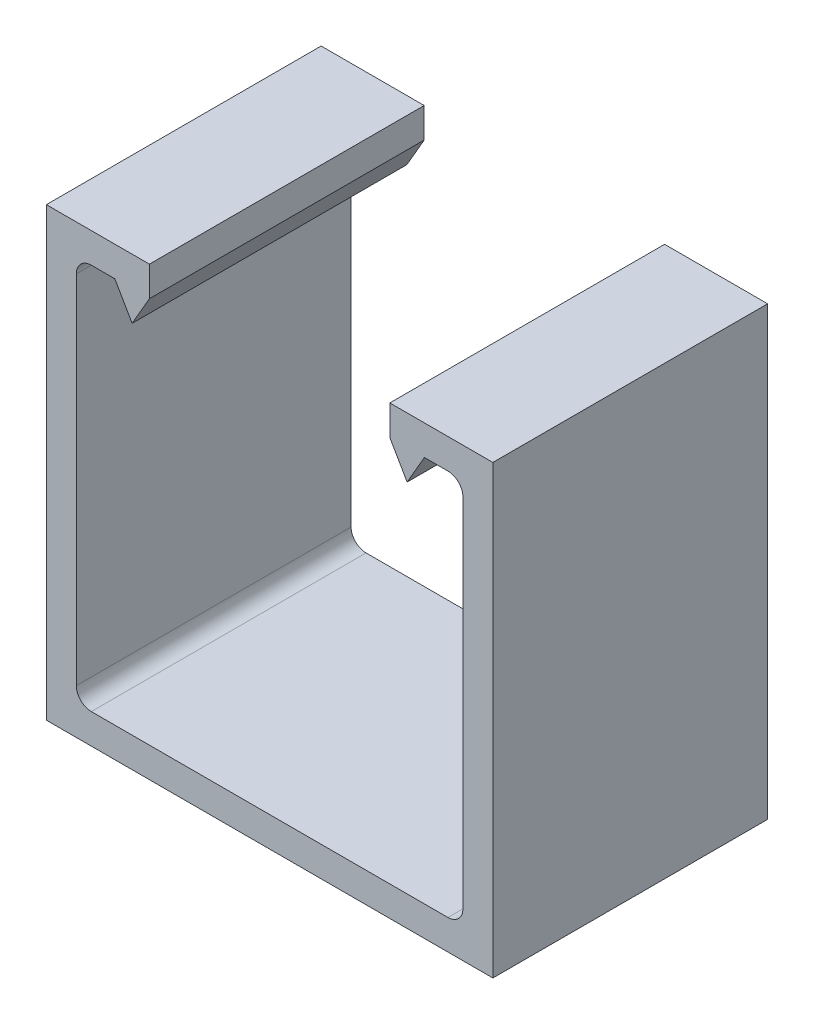
SolidWorks part; units mm, degrees
ref_plane "Plane1" through (0, 0, 0) normal (0, 0, 1) x (1, 0, 0)
ref_plane "Plane2" through (0, 0, 0) normal (0, 1, 0) x (1, 0, 0)
ref_plane "Plane3" through (0, 0, 0) normal (1, 0, 0) x (0, 0, -1)
sketch "Sketch1" plane through (0, 0, 0) normal (0, 0, 1) x (1, 0, 0)
  line L0 (-11.1125, 20.6375) -> (-20.6375, 20.6375)
  line L1 (-20.6375, 20.6375) -> (-20.6375, -20.6375)
  line L2 (-20.6375, -20.6375) -> (20.6375, -20.6375)
  line L3 (20.6375, -20.6375) -> (20.6375, 20.6375)
  line L4 (20.6375, 20.6375) -> (11.1125, 20.6375)
  line L5 (16.4846, 17.8689) -> (14.3094, 17.8689)
  line L6 (17.8689, -16.4846) -> (17.8689, 16.4846)
  line L7 (-16.4846, -17.8689) -> (16.4846, -17.8689)
  line L8 (-17.8689, 16.4846) -> (-17.8689, -16.4846)
  line L9 (-14.3094, 17.8689) -> (-16.4846, 17.8689)
  line L10 (14.3094, 17.8689) -> (12.711, 15.1003)
  line L11 (12.711, 15.1003) -> (11.1125, 17.8689)
  line L12 (11.1125, 17.8689) -> (11.1125, 20.6375)
  line L13 (-14.3094, 17.8689) -> (-12.711, 15.1003)
  line L14 (-12.711, 15.1003) -> (-11.1125, 17.8689)
  line L15 (-11.1125, 17.8689) -> (-11.1125, 20.6375)
  arc A0 (-17.8689, -16.4846) -> (-16.4846, -17.8689) centre (-16.4846, -16.4846) ccw
  arc A1 (-16.4846, 17.8689) -> (-17.8689, 16.4846) centre (-16.4846, 16.4846) ccw
  arc A2 (17.8689, 16.4846) -> (16.4846, 17.8689) centre (16.4846, 16.4846) ccw
  arc A3 (16.4846, -17.8689) -> (17.8689, -16.4846) centre (16.4846, -16.4846) ccw
  dimension "D5" = 1.3843
  dimension "Width" = 41.275
  dimension "Height" = 41.275
  dimension "D8" = 20.6375
  dimension "D9" = 20.6375
  dimension "D10" = 22.225
  dimension "edge" = 9.525
  dimension "D13" = 1.5985
  dimension "D4" = 60
extrude "Base-Extrude" add sketch "Sketch1" along normal mid plane 25.4
equation "\"D8@Sketch1\" = \"Width@Sketch1\" / 2"
equation "\"D9@Sketch1\" = \"Height@Sketch1\" / 2"
equation "\"D10@Sketch1\" = \"Width@Sketch1\" - 2 * \"edge@Sketch1\""
equation "\"D5@Sketch1\" = \"gauge@Sketch1\" / 2"
equation "\"D13@Sketch1\" = \"gauge@Sketch1\" * .577350269"
